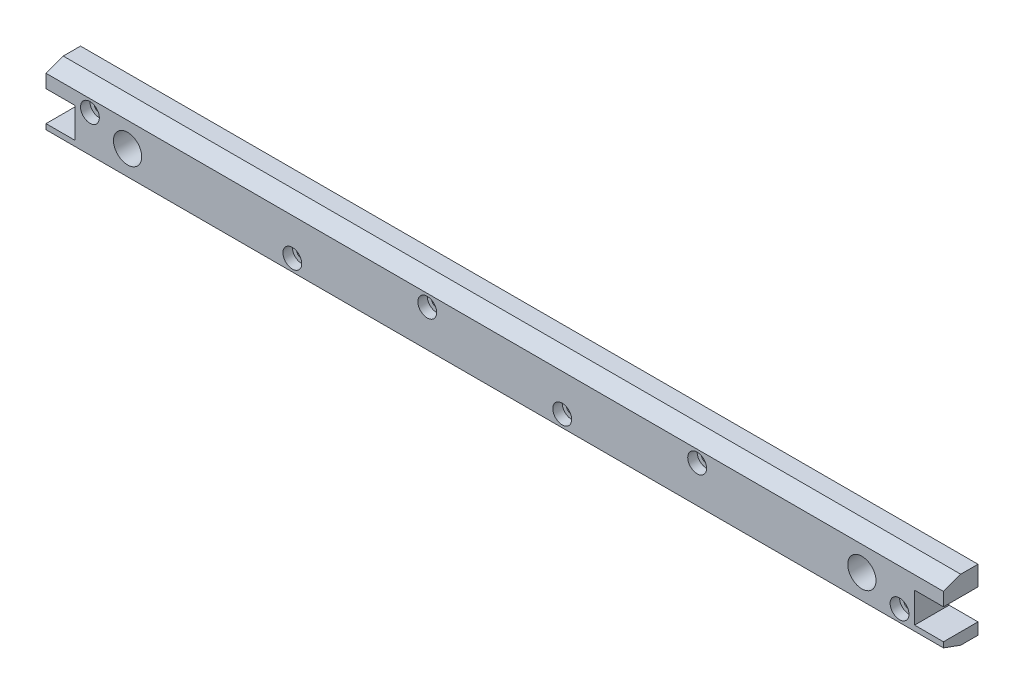
SolidWorks part; units mm, degrees
material "ABS"
ref_plane "Ebene vorne" through (0, 0, 0) normal (0, 0, 1) x (1, 0, 0)
ref_plane "Ebene oben" through (0, 0, 0) normal (0, 1, 0) x (1, 0, 0)
ref_plane "Ebene rechts" through (0, 0, 0) normal (1, 0, 0) x (0, 0, -1)
sketch "Skizze1" plane through (0, 0, 0) normal (0, 1, 0) x (1, 0, 0)
  line L0 (286, 0) -> (286, -6.26)
  line L1 (0, 0) -> (286, 0)
  line L2 (286, -6.26) -> (276.8, -6.26)
  line L3 (0, -19.6) -> (286, -19.6)
  line L4 (276.8, -6.26) -> (276.8, -15.9)
  line L5 (276.8, -15.9) -> (286, -15.9)
  line L6 (286, -15.9) -> (286, -19.6)
  line L7 (264.5, -9.8) -> (264.5, -19.6) construction
  line L8 (143, 0) -> (143, -19.6) construction
  line L9 (0, 0) -> (0, -6.26)
  line L10 (0, -6.26) -> (9.2, -6.26)
  line L11 (9.2, -6.26) -> (9.2, -15.9)
  line L12 (9.2, -15.9) -> (0, -15.9)
  line L13 (0, -15.9) -> (0, -19.6)
  line L14 (260, 0) -> (260, -19.6) construction
  line L15 (255.5, -9.8) -> (255.5, -19.6) construction
  line L16 (21.5, -9.8) -> (21.5, -19.6) construction
  line L17 (30.5, -9.8) -> (30.5, -19.6) construction
  line L18 (200.3301, -2.3) -> (204.6603, -9.8)
  line L19 (171.6699, -2.3) -> (200.3301, -2.3)
  line L20 (167.3397, -9.8) -> (171.6699, -2.3)
  line L21 (171.6699, -17.3) -> (167.3397, -9.8)
  line L22 (200.3301, -17.3) -> (171.6699, -17.3)
  line L23 (204.6603, -9.8) -> (200.3301, -17.3)
  line L24 (243.3301, -2.3) -> (247.6603, -9.8)
  line L25 (214.6699, -2.3) -> (243.3301, -2.3)
  line L26 (210.3397, -9.8) -> (214.6699, -2.3)
  line L27 (214.6699, -17.3) -> (210.3397, -9.8)
  line L28 (243.3301, -17.3) -> (214.6699, -17.3)
  line L29 (247.6603, -9.8) -> (243.3301, -17.3)
  line L30 (81.3397, -9.8) -> (85.6699, -2.3)
  line L31 (85.6699, -17.3) -> (81.3397, -9.8)
  line L32 (85.6699, -2.3) -> (114.3301, -2.3)
  line L33 (114.3301, -2.3) -> (118.6603, -9.8)
  line L34 (118.6603, -9.8) -> (114.3301, -17.3)
  line L35 (114.3301, -17.3) -> (85.6699, -17.3)
  line L36 (38.3397, -9.8) -> (42.6699, -2.3)
  line L37 (42.6699, -17.3) -> (38.3397, -9.8)
  line L38 (128.6699, -2.3) -> (157.3301, -2.3)
  line L39 (157.3301, -2.3) -> (161.6603, -9.8)
  line L40 (161.6603, -9.8) -> (157.3301, -17.3)
  line L41 (157.3301, -17.3) -> (128.6699, -17.3)
  line L42 (128.6699, -17.3) -> (124.3397, -9.8)
  line L43 (124.3397, -9.8) -> (128.6699, -2.3)
  line L44 (161.6603, -9.8) -> (124.3397, -9.8) construction
  line L45 (133, -9.8) -> (126.5048, -6.05) construction
  line L46 (153, -9.8) -> (159.4952, -6.05) construction
  line L47 (42.6699, -2.3) -> (71.3301, -2.3)
  line L48 (71.3301, -2.3) -> (75.6603, -9.8)
  line L49 (75.6603, -9.8) -> (71.3301, -17.3)
  line L50 (71.3301, -17.3) -> (42.6699, -17.3)
  line L51 (260, -9.8) -> (26, -9.8) construction
  line L52 (207.5, -5.8) -> (207.5, -9.8) construction
  line L53 (164.5, -13.8) -> (164.5, -9.8) construction
  line L54 (121.5, -5.8) -> (121.5, -9.8) construction
  line L55 (78.5, -9.8) -> (78.5, -13.8) construction
  line L56 (71.3301, -2.3) -> (214.6699, -2.3) construction
  circle A0 centre (260, -9.8) radius 4.5
  circle A1 centre (26, -9.8) radius 4.5
  circle A2 centre (14, -5.8) radius 1.65
  circle A3 centre (78.5, -13.8) radius 1.65
  circle A4 centre (121.5, -5.8) radius 1.65
  circle A5 centre (164.5, -13.8) radius 1.65
  circle A6 centre (207.5, -5.8) radius 1.65
  circle A7 centre (272, -13.8) radius 1.65
  circle A8 centre (260, -9.8) radius 7.6 construction
  point P62 (153, -9.8)
  point P93 (143, -9.8)
  dimension "D7" = 9
  dimension "D15" = 3.3
  dimension "D20" = 15.2
  dimension "D1" = 19.6
  dimension "D2" = 286
  dimension "D3" = 6.26
  dimension "D4" = 3.7
  dimension "D5" = 9.2
  dimension "D6" = 26
  dimension "D8" = 120
  dimension "D9" = 15
  dimension "D10" = 3
  dimension "D11" = 3
  dimension "D12" = 4
  dimension "D13" = 20
  dimension "D14" = 4
  dimension "D16" = 14
  dimension "D17" = 14
  dimension "D18" = 43
  dimension "D19" = 43
extrude "Aufsatz-Linear austragen1" add sketch "Skizze1" along normal blind 8 contours L16 A1 L17 L3 L15 A0 L7 L6 L5 L4 L2 L0 L1 L9 L10 L11 L12 L13 A7 A6 A5 A4 A3 A2 L42 L43 L38 L39 L40 L41 L24 L29 L28 L27 L26 L25 L18 L23 L22 L21
sketch "Skizze2" plane through (0, 8, 0) normal (0, 1, 0) x (1, 0, 0)
  line L20 (0, -19.6) -> (286, -19.6)
  line L24 (286, -19.6) -> (286, -15.9)
  line L25 (286, -15.9) -> (276.8, -15.9)
  line L26 (276.8, -15.9) -> (276.8, -6.26)
  line L27 (276.8, -6.26) -> (286, -6.26)
  line L28 (286, -6.26) -> (286, 0)
  line L29 (286, 0) -> (0, 0)
  line L30 (0, 0) -> (0, -6.26)
  line L31 (0, -6.26) -> (9.2, -6.26)
  line L32 (9.2, -6.26) -> (9.2, -15.9)
  line L33 (9.2, -15.9) -> (0, -15.9)
  line L34 (0, -15.9) -> (0, -19.6)
  line L38 (0, -19.6) -> (286, -19.6)
  line L42 (286, -19.6) -> (286, -15.9)
  line L43 (286, -15.9) -> (276.8, -15.9)
  line L44 (276.8, -15.9) -> (276.8, -6.26)
  line L45 (276.8, -6.26) -> (286, -6.26)
  line L46 (286, -6.26) -> (286, 0)
  line L47 (286, 0) -> (0, 0)
  line L48 (0, 0) -> (0, -6.26)
  line L49 (0, -6.26) -> (9.2, -6.26)
  line L50 (9.2, -6.26) -> (9.2, -15.9)
  line L51 (9.2, -15.9) -> (0, -15.9)
  line L52 (0, -15.9) -> (0, -19.6)
  circle A0 centre (272, -13.8) radius 1.65 construction
  circle A1 centre (207.5, -5.8) radius 1.65 construction
  circle A2 centre (260, -9.8) radius 4.5 construction
  circle A3 centre (26, -9.8) radius 4.5 construction
  circle A4 centre (260, -9.8) radius 4.5
  circle A5 centre (26, -9.8) radius 4.5
  circle A6 centre (164.5, -13.8) radius 1.65 construction
  circle A7 centre (78.5, -13.8) radius 1.65 construction
  circle A8 centre (121.5, -5.8) radius 1.65 construction
  circle A9 centre (14, -5.8) radius 1.65 construction
  circle A10 centre (272, -13.8) radius 1.65
  circle A11 centre (207.5, -5.8) radius 1.65
  circle A12 centre (164.5, -13.8) radius 1.65
  circle A13 centre (78.5, -13.8) radius 1.65
  circle A14 centre (121.5, -5.8) radius 1.65
  circle A15 centre (14, -5.8) radius 1.65
  dimension "D1" = 0
extrude "Aufsatz-Linear austragen2" add sketch "Skizze2" along normal offset from surface (3 mm away) 11 up to face at (272, 0, 15.45)
chamfer "Fase1" distance 2 angle 70 2 edges at (143, 11, 0) (143, 11, 19.6)
sketch "Skizze3" plane through (0, 11, 0) normal (0, 1, 0) x (1, 0, 0)
  circle A6 centre (14, -5.8) radius 3
  circle A7 centre (78.5, -13.8) radius 3
  circle A8 centre (121.5, -5.8) radius 3
  circle A9 centre (164.5, -13.8) radius 3
  circle A10 centre (207.5, -5.8) radius 3
  circle A11 centre (272, -13.8) radius 3
  dimension "D1" = 6
extrude "Schnitt-Linear austragen1" cut sketch "Skizze3" against normal blind 3
move or copy body "Körper-Verschieben/Kopieren1" bodies to move or copy 103 copy no rotation origin (0, 5.5, 9.8) rotation axis (1, 0, 0) rotation angle 90
